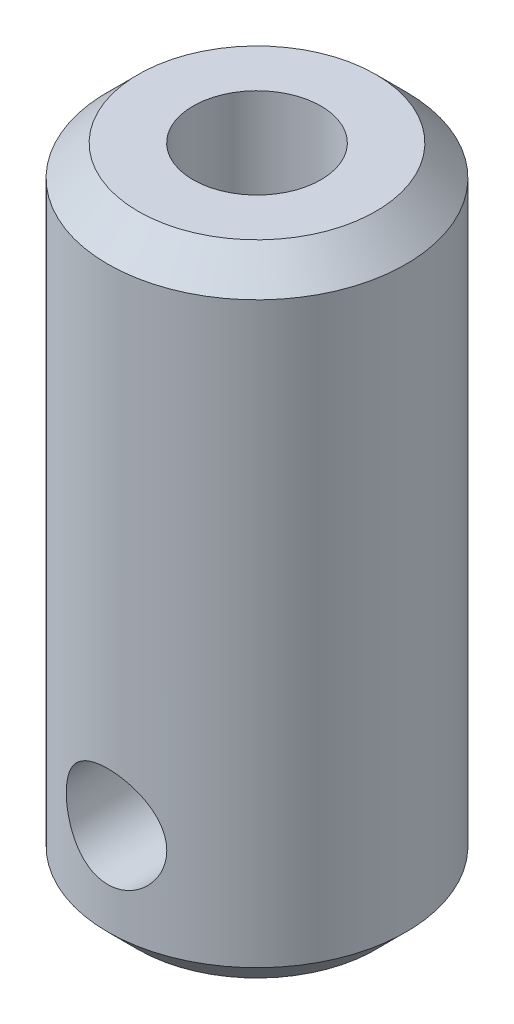
SolidWorks part; units mm, degrees
material "6061 合金"
ref_plane "前视基准面" through (0, 0, 0) normal (0, 0, 1) x (1, 0, 0)
ref_plane "上视基准面" through (0, 0, 0) normal (0, 1, 0) x (1, 0, 0)
ref_plane "右视基准面" through (0, 0, 0) normal (1, 0, 0) x (0, 0, -1)
sketch "草图1" plane through (0, 0, 0) normal (0, 1, 0) x (1, 0, 0)
  circle A0 centre (0, 0) radius 4.9
  dimension "D1" = 9.8
extrude "凸台-拉伸1" add sketch "草图1" along normal blind 21
ref_plane "基准面1" through (0, 0, 4.9) normal (0, 0, 1) x (1, 0, 0)
hole_wizard "M4 螺纹孔1" positions "草图2" profile "草图3" tap size "M4" standard "GB" end condition through all
sketch "草图2" plane through (0, 0, 4.9) normal (0, 0, 1) x (1, 0, 0)
  line L0 (-4.9, 0) -> (4.9, 0) construction
  point P0 (0, 4)
  dimension "D1" = 4
sketch "草图3" plane through (0, 4, 4.9) normal (1, 0, 0) x (0, -1, 0)
  line L0 (0, 0) -> (0, 9.8)
  line L1 (0, 9.8) -> (1.65, 9.8)
  line L2 (1.65, 9.8) -> (1.65, 0)
  line L5 (1.65, 0) -> (0, 0)
  line L11 (0, -6.35) -> (0, 107.95) construction
  dimension "通孔螺纹孔钻头直径" = 3.3
  dimension "通孔螺纹孔钻头深度" = 9.8
cosmetic thread "孔螺蚊线1" parameters "D2"=4
hole_wizard "M5 螺纹孔1" positions "草图4" profile "草图5" tap size "M5" standard "GB"
sketch "草图4" plane through (0, 21, 0) normal (0, 1, 0) x (1, 0, 0)
  point P0 (0, 0)
cosmetic thread "孔螺蚊线2" parameters "D1"=11, "D2"=5
sketch "草图5" plane through (0, 21, 0) normal (1, 0, 0) x (0, 0, 1)
  line L0 (0, 0) -> (0, 13.2618)
  line L1 (0, 13.2618) -> (2.1, 12)
  line L2 (2.1, 12) -> (2.1, 0)
  line L5 (2.1, 0) -> (0, 0)
  line L10 (0, 13.2618) -> (-2.1, 12) construction
  line L11 (0, -6.35) -> (0, 107.95) construction
  dimension "螺纹孔钻头直径" = 4.2
  dimension "螺纹孔钻头深度" = 12
  dimension "导头角度" = 118
chamfer "倒角1" distance 1 angle 45 2 edges at (0, 0, 4.9) (0, 21, 4.9)
